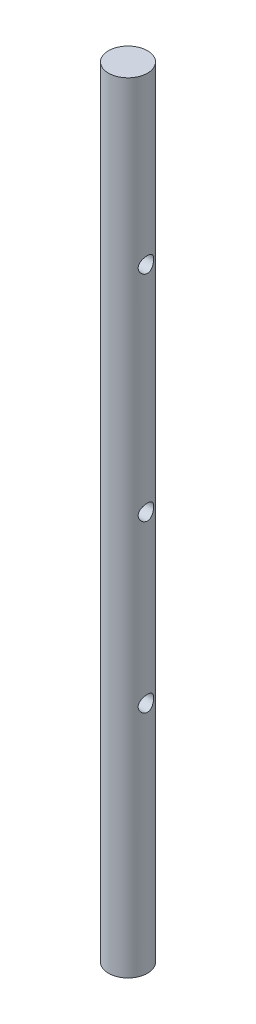
SolidWorks part; units mm, degrees
material "Brass"
ref_plane "Front Plane" through (0, 0, 0) normal (0, 0, 1) x (1, 0, 0)
ref_plane "Top Plane" through (0, 0, 0) normal (0, 1, 0) x (1, 0, 0)
ref_plane "Right Plane" through (0, 0, 0) normal (1, 0, 0) x (0, 0, -1)
sketch "Sketch1" plane through (0, 0, 0) normal (0, 1, 0) x (1, 0, 0)
  circle A1 centre (0, 0) radius 2
  dimension "D2" = 4
extrude "Boss-Extrude1" add sketch "Sketch1" along normal mid plane 80
sketch "Sketch3" plane through (0, 0, 0) normal (1, 0, 0) x (0, 0, -1)
  line L0 (2, 40) -> (-2, 40) construction
  circle A2 centre (0, 1) radius 0.7937
  circle A3 centre (0, 23) radius 0.7938
  dimension "D1" = 22
  dimension "D2" = 17
extrude "Cut-Extrude1" cut sketch "Sketch3" against normal mid plane 10
sketch "Sketch4" plane through (0, 0, 0) normal (1, 0, 0) x (0, 0, -1)
  circle A1 centre (0, -16) radius 0.7937
  circle A2 centre (0, -16) radius 0.7937
  dimension "D1" = 0
extrude "Cut-Extrude2" cut sketch "Sketch4" against normal mid plane 10
